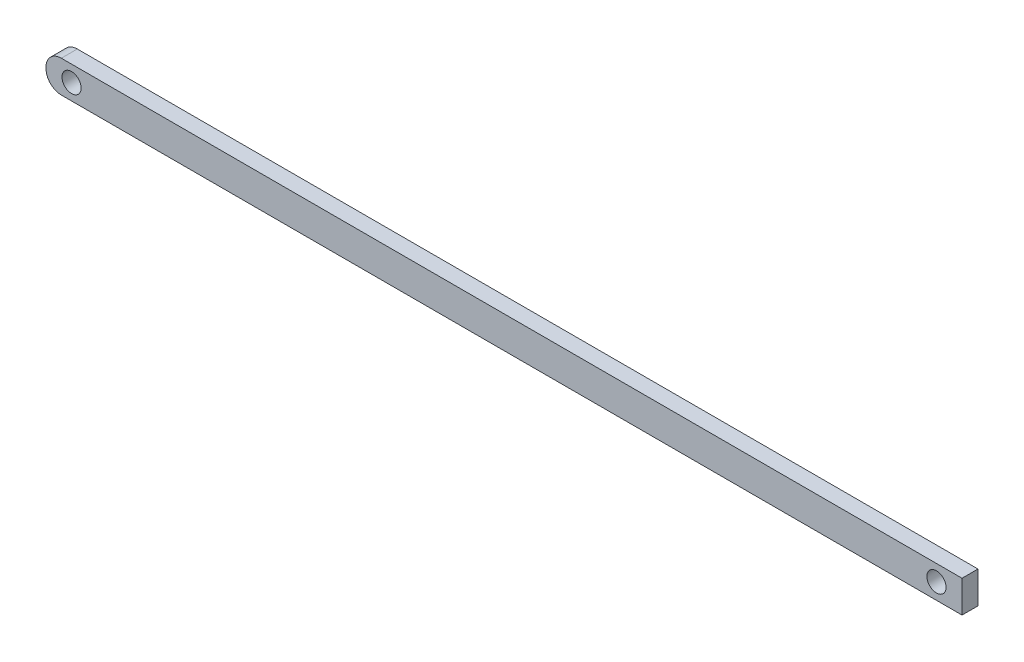
SolidWorks part; units mm, degrees
ref_plane "Front Plane" through (0, 0, 0) normal (0, 0, 1) x (1, 0, 0)
ref_plane "Top Plane" through (0, 0, 0) normal (0, 1, 0) x (1, 0, 0)
ref_plane "Right Plane" through (0, 0, 0) normal (1, 0, 0) x (0, 0, -1)
sketch "Sketch1" plane through (0, 0, 0) normal (0, 0, 1) x (1, 0, 0)
  line L0 (-571.4963, 0) -> (529.423, 0) construction
  line L1 (0, 269.0941) -> (0, -345.3521) construction
  line L3 (-358.5, 12.5) -> (358.5, 12.5)
  line L4 (-358.5, 12.5) -> (-358.5, -12.5)
  line L5 (-358.5, -12.5) -> (358.5, -12.5)
  line L6 (358.5, 12.5) -> (358.5, -12.5)
  circle A0 centre (-338.5, 0) radius 7.5
  circle A1 centre (338.5, 0) radius 7.5
  point P5 (0, 0)
  dimension "D3" = 15
  dimension "D4" = 15
  dimension "D1" = 717
  dimension "D2" = 25
  dimension "D5" = 338.5
  dimension "D6" = 338.5
extrude "Boss-Extrude1" add sketch "Sketch1" along normal blind 25
fillet "Fillet1" radius 12 2 edges at (-358.5, -12.5, 12.5) (-358.5, 12.5, 12.5)
sketch "Sketch2" plane through (358.5, 0, 0) normal (1, 0, 0) x (0, 0, -1)
  line L0 (-48.9469, 0) -> (43.508, 0) construction
  line L1 (0, 20.7937) -> (0, -31.1817) construction
  line L2 (0, 12.5) -> (-12.5, 12.5)
  line L3 (-25, 12.5) -> (0, 12.5) construction
  line L4 (-12.5, 12.5) -> (-12.5, -12.5)
  line L5 (-25, -12.5) -> (0, -12.5) construction
  line L6 (-12.5, -12.5) -> (0, -12.5)
  line L7 (0, -12.5) -> (0, 12.5)
extrude "Cut-Extrude1" cut sketch "Sketch2" against normal through all both and the other way through all
